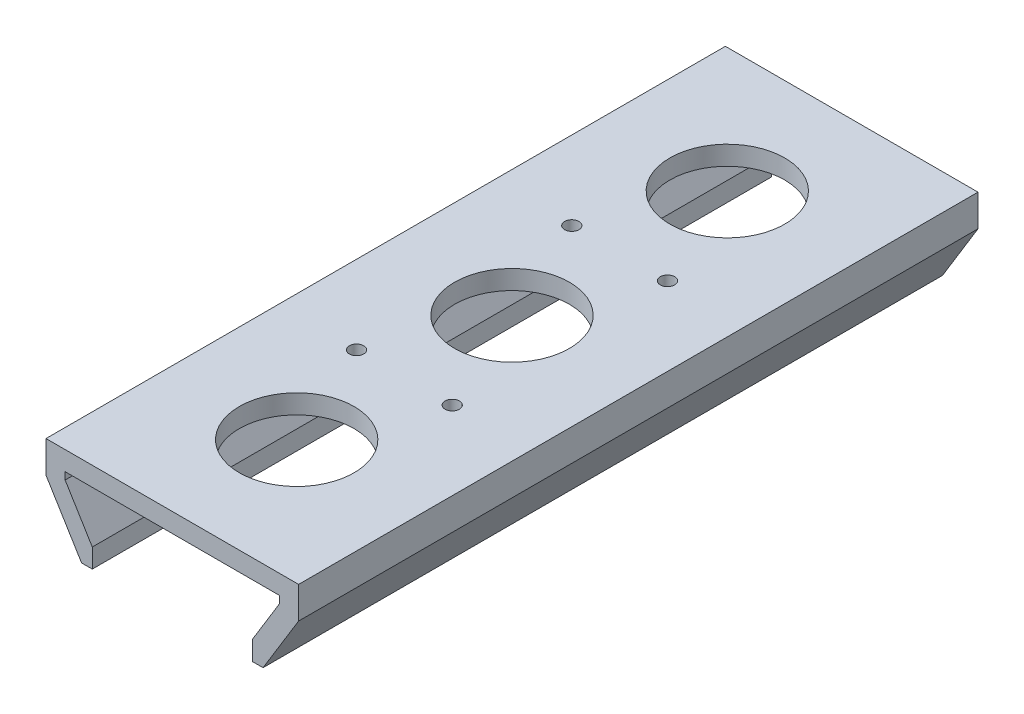
SolidWorks part; units mm, degrees
ref_plane "Płaszczyzna przednia" through (0, 0, 0) normal (0, 0, 1) x (1, 0, 0)
ref_plane "Płaszczyzna górna" through (0, 0, 0) normal (0, 1, 0) x (1, 0, 0)
ref_plane "Płaszczyzna prawa" through (0, 0, 0) normal (1, 0, 0) x (0, 0, -1)
sketch "Sketch1" plane through (0, 0, 0) normal (0, 0, 1) x (1, 0, 0)
  line L0 (0, -13.0894) -> (0, -81.2091) construction
  line L1 (0, -13.4894) -> (22, -13.4894)
  line L2 (22, -13.4894) -> (22, -14.4894)
  line L3 (16.5, -23.4894) -> (0, -23.4894)
  line L4 (22, -14.4894) -> (16.5, -23.4894)
  line L5 (0, -13.4894) -> (0, -23.4894)
  line L6 (0, -13.0894) -> (22.4, -13.0894)
  line L7 (22.4, -13.0894) -> (22.4, -14.6019)
  line L8 (22.4, -14.6019) -> (16.7243, -23.8894)
  line L9 (16.7243, -23.8894) -> (0, -23.8894)
  line L11 (18.9677, -27.8894) -> (16.7243, -27.8894)
  line L13 (-26.4, -9.0894) -> (26.4, -9.0894)
  line L14 (26.4, -9.0894) -> (26.4, -15.7274)
  line L15 (26.4, -15.7274) -> (18.9677, -27.8894)
  line L16 (0, -13.0894) -> (0, -31.461)
  line L17 (16.7243, -23.8894) -> (16.7243, -27.8894)
  line L18 (-4.4, -9.0894) -> (-4.4, -27.8894) construction
  line L20 (-4.4, -9.0894) -> (26.4, -9.0894) construction
  line L21 (18.9677, -27.8894) -> (-4.4, -27.8894) construction
  line L22 (-0.4, -13.0894) -> (-0.4, -23.8894) construction
  line L23 (16.7243, -23.8894) -> (-0.4, -23.8894) construction
  line L24 (-0.4, -13.0894) -> (22.4, -13.0894) construction
  line L25 (-26.4, -9.0894) -> (-26.4, -15.7274)
  line L26 (-26.4, -15.7274) -> (-18.9677, -27.8894)
  line L27 (-18.9677, -27.8894) -> (-16.7243, -27.8894)
  line L28 (-16.7243, -23.8894) -> (-16.7243, -27.8894)
  line L29 (-22.4, -14.6019) -> (-16.7243, -23.8894)
  line L30 (-22.4, -13.0894) -> (-22.4, -14.6019)
  line L31 (0, -13.0894) -> (-22.4, -13.0894)
  point P4 (22, -23.4894)
  dimension "D1" = 9
  dimension "D2" = 5.5
  dimension "D3" = 10
  dimension "D4" = 22
  dimension "D5" = 0.4
  dimension "D6" = 4
extrude "Boss-Extrude1" add sketch "Sketch1" along normal blind 142 contours L31 L6 L7 L8 L17 L11 L15 L14 L13 L25 L26 L27 L28 L29 L30
sketch "Sketch2" plane through (0, -9.0894, 0) normal (0, 1, 0) x (1, 0, 0)
  line L0 (0, 0) -> (0, -186.0262) construction
  line L1 (26.4, 0) -> (-26.4, -142) construction
  circle A0 centre (0, -26) radius 12
  circle A1 centre (0, -71) radius 12
  circle A2 centre (0, -116) radius 12
  point P12 (0, -71)
  dimension "D2" = 24
  dimension "D1" = 186.0262
  dimension "D5" = 45
  dimension "D4" = 3
extrude "Cut-Extrude1" cut sketch "Sketch2" against normal blind 213
sketch "Sketch3" plane through (0, -9.0894, 0) normal (0, 1, 0) x (1, 0, 0)
  line L0 (-41.0874, -71) -> (42.5248, -71) construction
  line L1 (0, -71) -> (0, -116) construction
  line L2 (-10, -93.5) -> (10, -93.5) construction
  line L3 (-10, -48.5) -> (10, -48.5) construction
  circle A0 centre (0, -71) radius 12
  circle A1 centre (0, -71) radius 12 construction
  circle A2 centre (0, -116) radius 12
  circle A3 centre (0, -116) radius 12 construction
  circle A4 centre (-10, -93.5) radius 1.5
  circle A5 centre (10, -93.5) radius 1.5
  circle A6 centre (10, -48.5) radius 1.5
  circle A7 centre (-10, -48.5) radius 1.5
  point P9 (0, -93.5)
  point P18 (0, -93.5)
  dimension "D2" = 3
  dimension "D1" = 20
extrude "Cut-Extrude2" cut sketch "Sketch3" against normal blind 10 contours A5 | A4 | A7 | A6
